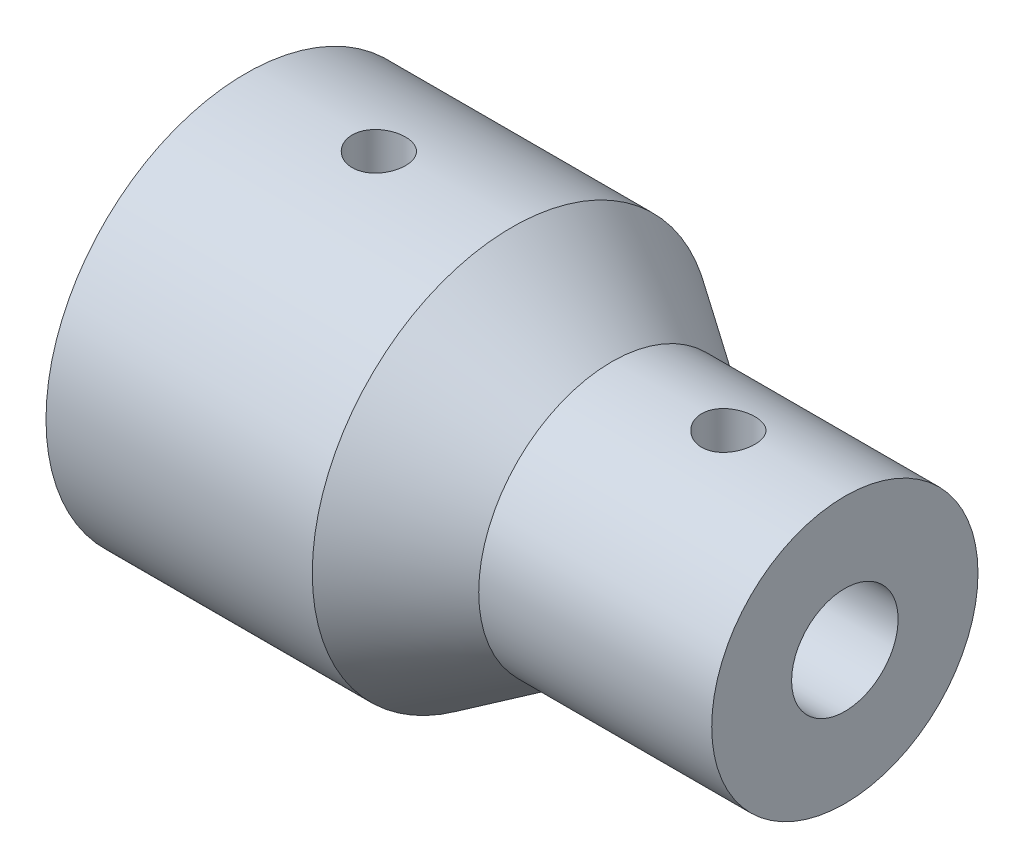
SolidWorks part; units mm, degrees
ref_plane "Front Plane" through (0, 0, 0) normal (0, 0, 1) x (1, 0, 0)
ref_plane "Top Plane" through (0, 0, 0) normal (0, 1, 0) x (1, 0, 0)
ref_plane "Right Plane" through (0, 0, 0) normal (1, 0, 0) x (0, 0, -1)
sketch "Sketch1" plane through (0, 0, 0) normal (0, 1, 0) x (1, 0, 0)
  line L0 (0, 0) -> (50114.9151, 0) construction
  line L1 (0, -1002.2983) -> (0, 0) construction
  line L2 (-10.16, 3.3655) -> (0, 3.3655)
  line L3 (0, 7.62) -> (3.81, 5.08)
  line L4 (-10.16, 3.3655) -> (-10.16, 7.62)
  line L5 (-10.16, 7.62) -> (0, 7.62)
  line L8 (12.7, 5.08) -> (12.7, 2.032)
  line L9 (0, 3.3655) -> (0, 50114.9151) construction
  line L10 (0, 3.3655) -> (2.3097, 2.032)
  line L11 (2.3097, 2.032) -> (12.7, 2.032)
  line L12 (3.81, 5.08) -> (12.7, 5.08)
  line L13 (0.4092, 3.3655) -> (50000.4092, 3.3655) construction
  line L14 (0, 7.62) -> (50000, 7.62) construction
  dimension "D1" = 4.064
  dimension "D2" = 6.731
  dimension "D3" = 30
  dimension "D4" = 15.24
  dimension "D5" = 10.16
  dimension "D6" = 22.86
  dimension "D7" = 10.16
  dimension "D8" = 3.81
revolve "Revolve1" add sketch "Sketch1" angle 360 about L0
sketch "Sketch2" plane through (0, 0, 0) normal (0, 1, 0) x (1, 0, 0)
  line L0 (0, 0) -> (50000, 0) construction
  line L1 (0, 7.62) -> (-10.16, 7.62) construction
  line L2 (-5.08, 7.62) -> (-5.08, 0) construction
  line L3 (8.255, 5.08) -> (8.255, 0) construction
  line L4 (12.7, 5.08) -> (3.81, 5.08) construction
  circle A0 centre (-5.08, 0) radius 1.016
  circle A1 centre (8.255, 0) radius 1.016
  point P13 (-6.3016, 0)
  point P16 (0, 0)
  dimension "D1" = 2.032
  dimension "D2" = 2.032
extrude "Cut-Extrude1" cut sketch "Sketch2" along normal through all
pattern_circular "CirPattern1" count 2 every 90 about axis through (-10.16, 0, 0) along (-1, 0, 0) of "Cut-Extrude1"
equation "\"D2@Sketch2\"=\"D1@Sketch2\""
